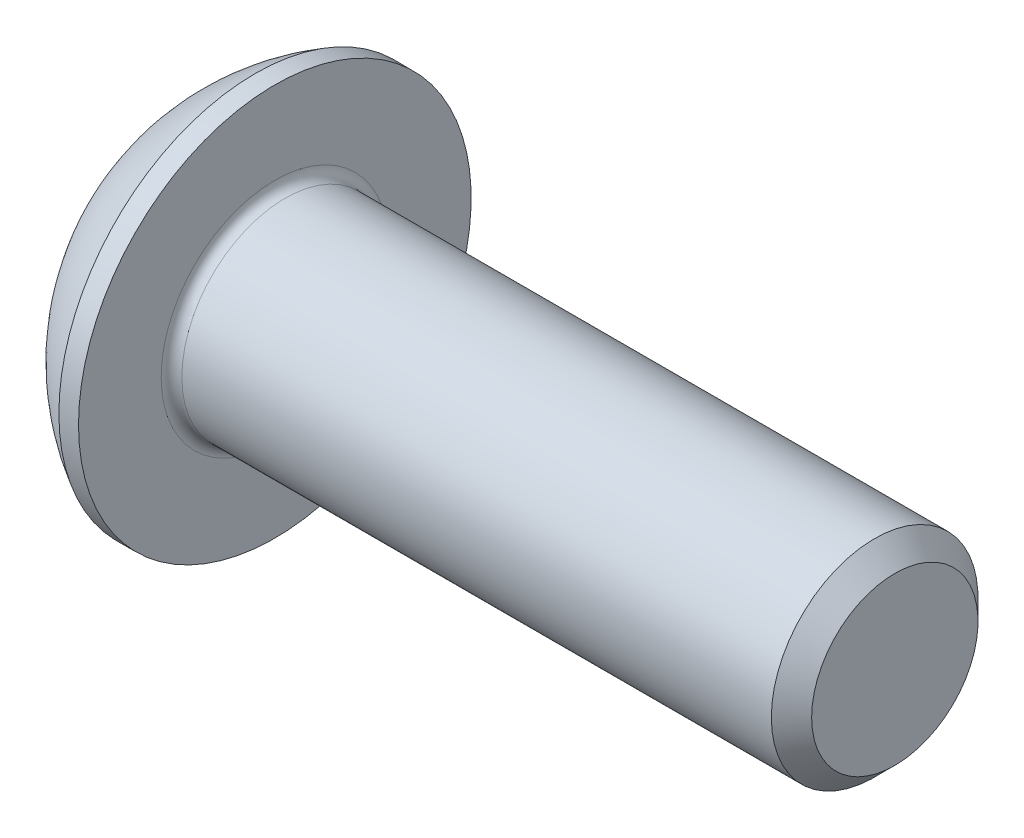
SolidWorks part; units mm, degrees
ref_plane "Plane1" through (0, 0, 0) normal (0, 0, 1) x (1, 0, 0)
ref_plane "Plane2" through (0, 0, 0) normal (0, 1, 0) x (1, 0, 0)
ref_plane "Plane3" through (0, 0, 0) normal (1, 0, 0) x (0, 0, -1)
sketch "BodySke" plane through (0, 0, 0) normal (0, 0, 1) x (1, 0, 0)
  line L0 (14.2, 0) -> (14.2, 1.61)
  line L1 (13.81, 2) -> (2.2, 2)
  line L2 (2.2, 2) -> (2.2, 3.8)
  line L3 (2.2, 3.8) -> (1.82, 3.8)
  line L4 (0, 0) -> (101.6, 0) construction
  line L5 (2.2, -3.8) -> (1.82, -3.8) construction
  line L6 (55.6768, -2) -> (2.2, -2) construction
  line L7 (14.2, 0) -> (0, 0)
  line L8 (0, 1.9) -> (0, -1.9) construction
  line L9 (0, 0) -> (0, 1.9)
  line L10 (14.2, 1.61) -> (13.81, 2)
  line L11 (14.2, -1.61) -> (13.81, -2) construction
  line L12 (2.9, 9.525) -> (2.9, -2) construction
  line L13 (2.2, 9.525) -> (2.2, -2) construction
  arc A1 (0, 1.9) -> (1.82, 3.8) centre (3.8853, 0) cw
  dimension "D1" = 3.8
  dimension "Diameter" = 4
  dimension "Length" = 12
  dimension "Head_dia" = 7.6
  dimension "Head_ht" = 2.2
  dimension "Head_side_ht" = 0.38
  dimension "Minor_dia" = 3.22
  dimension "Body_ch_ang" = 45
  dimension "Advance" = 0.7
  dimension "Thread_nom" = 12
revolve "BaseBody" add sketch "BodySke" angle 360 about L4
cosmetic thread "ThreadCosmetic" [suppressed] parameters "Thread_length"=10.6, "Thread_minor"=3.22
fillet "Fillet1" radius 0.2 1 edges at (2.2, 0, 2)
sketch "Sketch2" plane through (0, 0, 0) normal (0, 0, 1) x (1, 0, 0)
  line L0 (0, 1.25) -> (1.3, 1.25)
  line L1 (1.3, 1.25) -> (2.0217, 0)
  line L3 (2.0217, 0) -> (0, 0)
  line L4 (0, 0) -> (0, 1.25)
  line L5 (0, -1.25) -> (1.3, -1.25) construction
  line L6 (0, 0) -> (47.625, 0) construction
  dimension "D2" = 60
  dimension "PreBroach_depth" = 1.3
  dimension "PreBroach_dia" = 2.5
revolve "PreBroach" cut sketch "Sketch2" angle 360 about L6
sketch "Sketch3" plane through (0, 0, 0) normal (1, 0, 0) x (0, 0, -1)
  line L0 (-1.25, -0.7217) -> (-1.25, 0.7217)
  line L1 (-1.25, 0.7217) -> (0, 1.4434)
  line L2 (0, 1.4434) -> (1.25, 0.7217)
  line L3 (1.25, 0.7217) -> (1.25, -0.7217)
  line L4 (1.25, -0.7217) -> (0, -1.4434)
  line L5 (0, -1.4434) -> (-1.25, -0.7217)
  dimension "D1" = 1.25
  dimension "D2" = 1.25
  dimension "D3" = 2.5
  dimension "Hex_size" = 2.5
extrude "Hex" cut sketch "Sketch3" along normal blind 1.3
sketch "ThdSchSke" plane through (0, 0, 0) normal (0, 0, 1) x (1, 0, 0)
  line L0 (3.6, -1.61) -> (3.3269, -2)
  line L1 (3.6, -1.61) -> (3.8731, -2)
  line L2 (3.8731, -2) -> (3.8731, -2.5)
  line L3 (-3.175, 0) -> (5.1513, 0) construction
  line L5 (3.8731, -2.5) -> (3.3269, -2.5)
  line L6 (3.3269, -2.5) -> (3.3269, -2)
  dimension "Thread_minor" = 3.22
  dimension "Diameter" = 4
  dimension "Start" = 3.6
  dimension "SideAngle" = 55
  dimension "VeeAngle" = 70
  dimension "Overcut" = 5
revolve "ThreadSchematic" [suppressed] cut sketch "ThdSchSke" angle 360 about L3
pattern_linear "ThdSchPat" [suppressed]
equation "\"D1@BodySke\" = \"Head_dia@BodySke\" * .5"
equation "\"Thread_minor@ThreadCosmetic\" = \"Minor_dia@BodySke\""
equation "\"D1@Sketch3\" = \"Hex_size@Sketch3\" / 2"
equation "\"D2@Sketch3\" = \"D1@Sketch3\""
equation "\"D3@Sketch3\" = \"Hex_size@Sketch3\""
equation "\"Thread_length@ThreadCosmetic\" = ((sgn( (\"Length@BodySke\" - \"Advance@BodySke\" * 2.0) - \"Thread_nom@BodySke\" )-1)*( (\"Length@BodySke\" - \"Advance@BodySke\" * 2.0) - \"Thread_nom@BodySke\" ))/-2+ \"Thread_nom@BodySke\""
equation "\"Thread_minor@ThdSchSke\" = \"Minor_dia@BodySke\""
equation "\"Diameter@ThdSchSke\" = \"Diameter@BodySke\""
equation "\"Overcut@ThdSchSke\" = \"Diameter@BodySke\" * 1.25"
equation "\"Start@ThdSchSke\" = \"Head_ht@BodySke\" + \"Length@BodySke\" - \"Thread_length@ThreadCosmetic\"  '---Non-countersunk---"
equation "\"Num_threads@ThdSchPat\" = int( \"Thread_length@ThreadCosmetic\" / \"Advance@BodySke\" + 0.999 )  + 1"
equation "\"Advance@ThdSchPat\" = \"Thread_length@ThreadCosmetic\" /  (\"Num_threads@ThdSchPat\" - 1) 'relax it"
equation "\"Num_threads@ThdSchPat\" = \"Num_threads@ThdSchPat\" - sgn( \"Num_threads@ThdSchPat\" - 1) '---chamfered tips only---"
